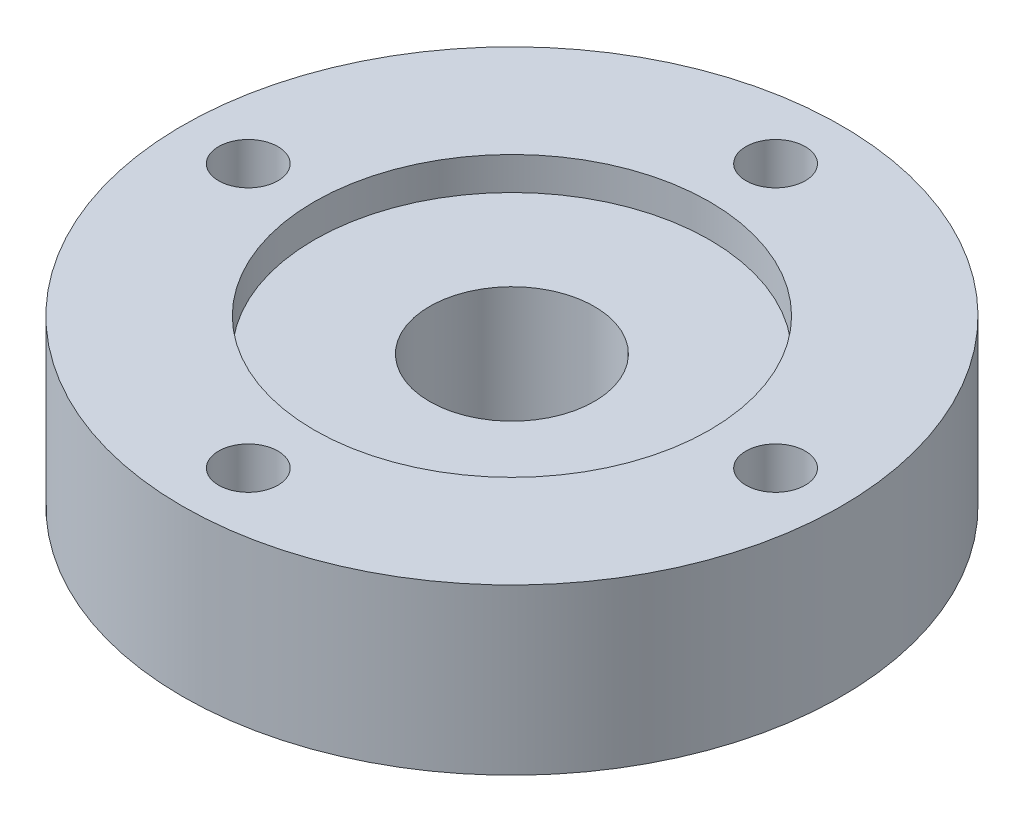
SolidWorks part; units mm, degrees
ref_plane "前视基准面" through (0, 0, 0) normal (0, 0, 1) x (1, 0, 0)
ref_plane "上视基准面" through (0, 0, 0) normal (0, 1, 0) x (1, 0, 0)
ref_plane "右视基准面" through (0, 0, 0) normal (1, 0, 0) x (0, 0, -1)
other "Configuration Table"
sketch "草图1" plane through (0, 0, 0) normal (0, 1, 0) x (1, 0, 0)
  circle A0 centre (0, 0) radius 10
  circle A1 centre (0, 0) radius 2.5
extrude "凸台-拉伸1" add sketch "草图1" along normal blind 5
sketch "草图2" plane through (0, 5, 0) normal (0, 1, 0) x (1, 0, 0)
  circle A0 centre (0, 0) radius 6
extrude "切除-拉伸1" cut sketch "草图2" against normal blind 1
sketch "草图3" plane through (0, 5, 0) normal (0, 1, 0) x (1, 0, 0)
  circle A0 centre (0, 8) radius 0.9
  circle A1 centre (8, 0) radius 0.9
  circle A2 centre (0, -8) radius 0.9
  circle A3 centre (-8, 0) radius 0.9
  point P11 (0, 0)
  dimension "D1" = 4
extrude "切除-拉伸2" cut sketch "草图3" against normal through all
